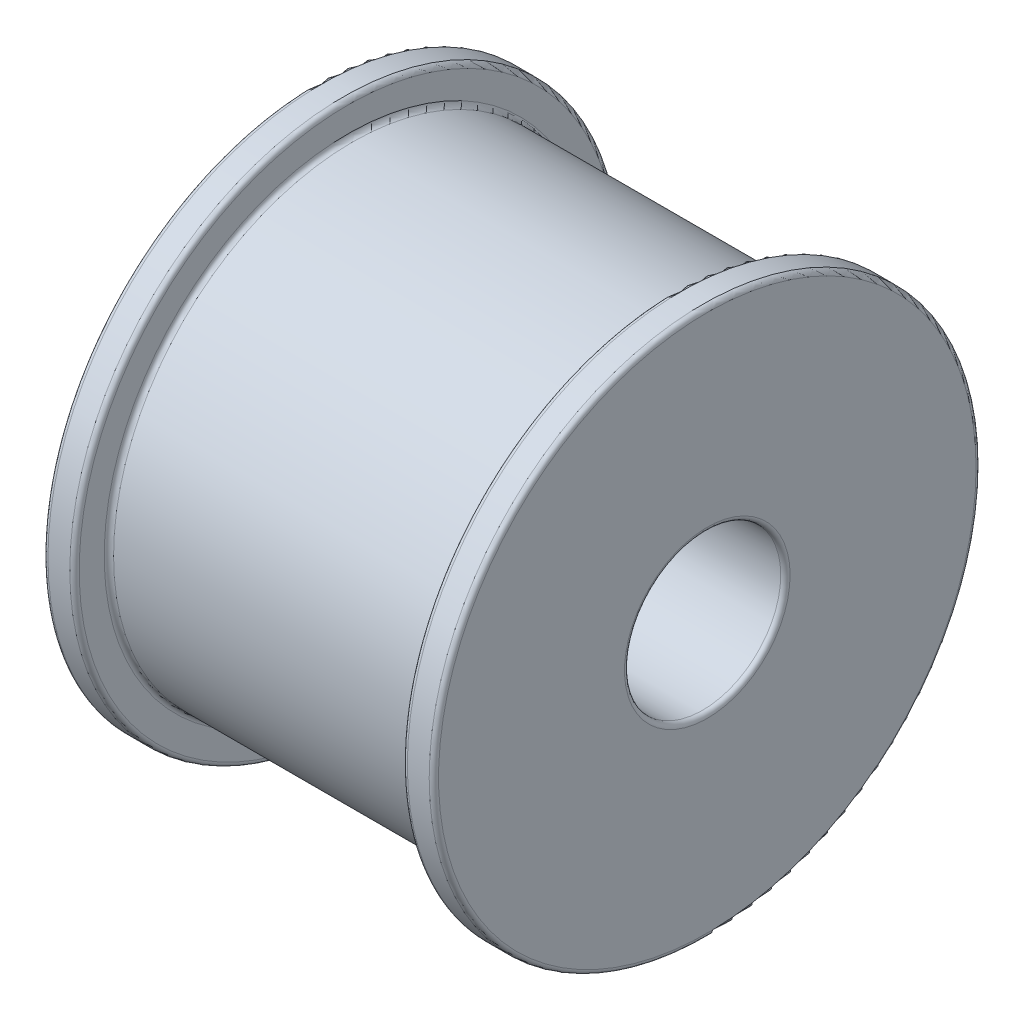
SolidWorks part; units mm, degrees
ref_plane "前视基准面" through (0, 0, 0) normal (0, 0, 1) x (1, 0, 0)
ref_plane "上视基准面" through (0, 0, 0) normal (0, 1, 0) x (1, 0, 0)
ref_plane "右视基准面" through (0, 0, 0) normal (1, 0, 0) x (0, 0, -1)
sketch "草图1" plane through (0, 0, 0) normal (1, 0, 0) x (0, 0, -1)
  circle A0 centre (0, 0) radius 17.5
  dimension "D1" = 35
extrude "凸台-拉伸1" add sketch "草图1" along normal blind 2
sketch "草图2" plane through (2, 0, 0) normal (1, 0, 0) x (0, 0, -1)
  circle A0 centre (0, 0) radius 15.3
  dimension "D1" = 30.6
extrude "凸台-拉伸2" add sketch "草图2" along normal blind 21
sketch "草图3" plane through (23, 0, 0) normal (1, 0, 0) x (0, 0, -1)
  circle A0 centre (0, 0) radius 17.5
  dimension "D1" = 35
extrude "凸台-拉伸3" add sketch "草图3" along normal blind 2
sketch "草图4" plane through (25, 0, 0) normal (1, 0, 0) x (0, 0, -1)
  circle A0 centre (0, 0) radius 5
  dimension "D1" = 10
extrude "切除-拉伸1" cut sketch "草图4" against normal through all
fillet "圆角1" radius 0.3 8 edges at (2, 0, -15.3) (23, 0, -15.3) (0, 0, -5) (25, 0, -5) (25, 0, -17.5) (23, 0, -17.5) (2, 0, -17.5) (0, 0, -17.5)
